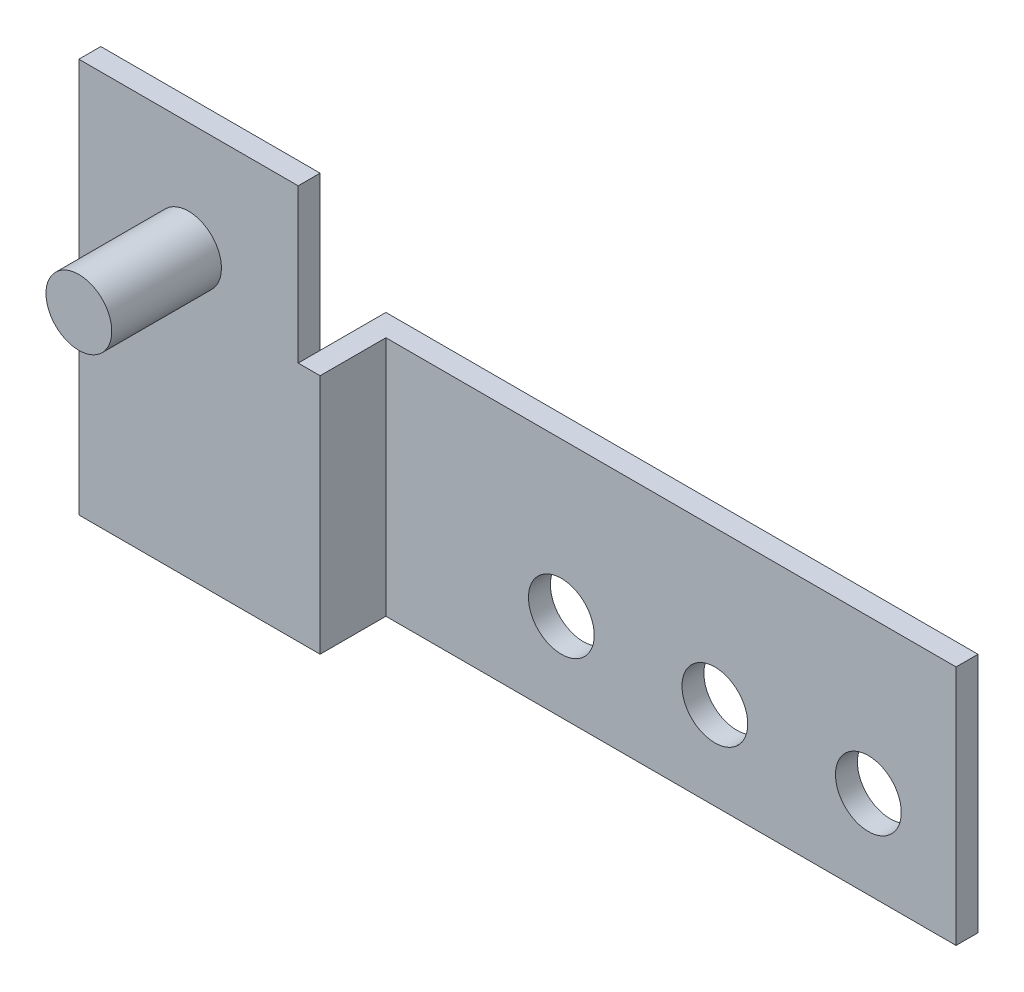
SolidWorks part; units mm, degrees
material "Обычная углеродистая сталь"
ref_plane "Спереди" through (0, 0, 0) normal (0, 0, 1) x (1, 0, 0)
ref_plane "Сверху" through (0, 0, 0) normal (0, 1, 0) x (1, 0, 0)
ref_plane "Справа" through (0, 0, 0) normal (1, 0, 0) x (0, 0, -1)
ref_plane "Плоскость4" through (0, 0, 3) normal (0, 0, -1) x (-1, 0, 0)
sketch "Эскиз1" plane through (0, 0, 3) normal (0, 0, -1) x (-1, 0, 0)
  line L0 (10, 18) -> (-27, 18)
  line L1 (-27, 18) -> (-27, 0)
  line L2 (-27, 0) -> (10, 0)
  line L3 (10, 0) -> (10, 18)
extrude "Бобышка-Вытянуть1" add sketch "Эскиз1" against normal blind 1
sketch "Эскиз2" plane through (0, 0, 4) normal (0, 0, 1) x (1, 0, 0)
  line L0 (27, 18) -> (0, 18)
  line L1 (0, 18) -> (0, 11)
  line L2 (0, 11) -> (27, 11)
  line L3 (27, 11) -> (27, 18)
extrude "Вырез-Вытянуть1" cut sketch "Эскиз2" against normal through all
sketch "Эскиз3" plane through (0, 0, 3) normal (0, 0, -1) x (-1, 0, 0)
  line L0 (0, 11) -> (0, 0)
  line L1 (0, 0) -> (-27, 0)
  line L2 (-27, 0) -> (-27, 11)
  line L3 (-27, 11) -> (0, 11)
extrude "Бобышка-Вытянуть2" add sketch "Эскиз3" along normal blind 3
sketch "Эскиз4" plane through (0, 0, 0) normal (0, -1, 0) x (1, 0, 0)
  line L0 (1, 4) -> (1, 1)
  line L1 (1, 1) -> (27, 1)
  line L2 (27, 1) -> (27, 4)
  line L3 (27, 4) -> (1, 4)
extrude "Вырез-Вытянуть2" cut sketch "Эскиз4" against normal through all
ref_plane "Плоскость5" through (0, 13, 0) normal (0, -1, 0) x (1, 0, 0)
sketch "Эскиз5" plane through (0, 13, 0) normal (0, -1, 0) x (1, 0, 0)
  line L0 (-3.5, 9) -> (-5, 9)
  line L1 (-5, 9) -> (-5, 4)
  line L2 (-5, 4) -> (-3.5, 4)
  line L3 (-3.5, 4) -> (-3.5, 9)
  line L4 (-5, 9) -> (-5, 4) construction
revolve "Повернуть1" add sketch "Эскиз5" angle 360 about L4
hole_wizard "Диаметр отверстия Ø3.0 (3)1" positions "Эскиз7" profile "Эскиз6" hole size "Ø3.0" standard "Ansi Metric"
sketch "Эскиз7" plane through (0, 0, 1) normal (0, 0, 1) x (1, 0, 0)
  point P0 (23, 4)
  point P1 (16, 4)
  point P2 (9, 4)
sketch "Эскиз6" plane through (23, 4, 1) normal (1, 0, 0) x (0, -1, 0)
  line L0 (0, 0) -> (0, 1)
  line L1 (0, 1) -> (1.5, 1)
  line L2 (1.5, 1) -> (1.5, 0)
  line L5 (1.5, 0) -> (0, 0)
  line L11 (0, -6.35) -> (0, 107.95) construction
  dimension "Диаметр сквозного отверстия" = 3
  dimension "Глубина сквозного отверстия" = 1
